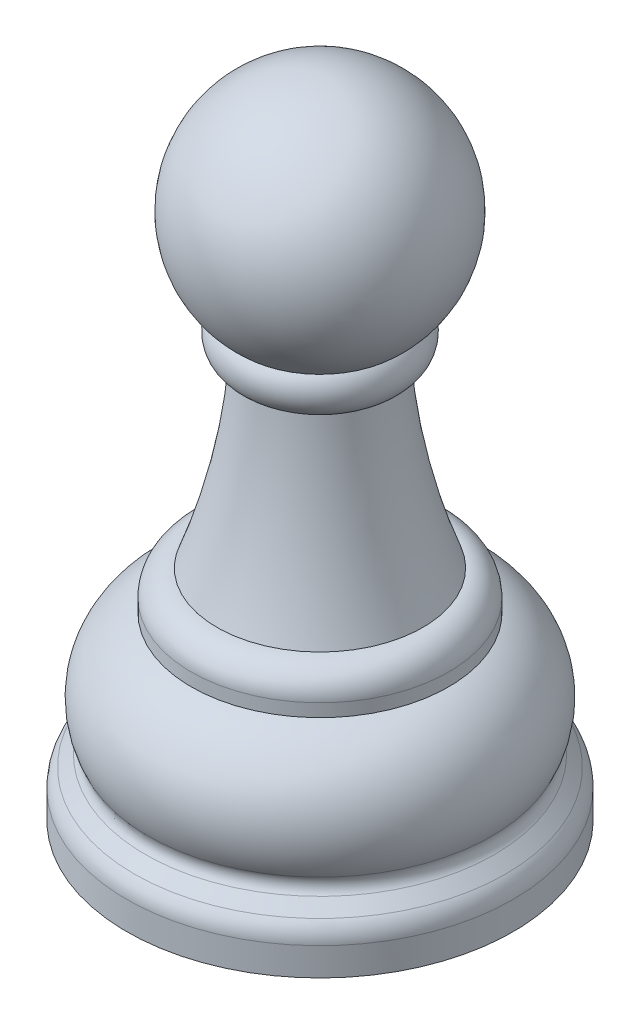
SolidWorks part; units mm, degrees
ref_plane "Front Plane" through (0, 0, 0) normal (0, 0, 1) x (1, 0, 0)
ref_plane "Top Plane" through (0, 0, 0) normal (0, 1, 0) x (1, 0, 0)
ref_plane "Right Plane" through (0, 0, 0) normal (1, 0, 0) x (0, 0, -1)
sketch "Sketch1" plane through (0, 0, 0) normal (0, 0, 1) x (1, 0, 0)
  line L0 (0, 0) -> (0, -50)
  line L1 (0, -50) -> (13, -50)
  line L4 (13, -45) -> (15, -47)
  line L5 (15, -47) -> (15, -50)
  line L6 (15, -50) -> (13, -50)
  line L12 (10, -36.03) -> (10, -35.03)
  arc A0 (10, -36.03) -> (13, -45) centre (8, -41.6856) cw
  arc A1 (8, -33.03) -> (10, -35.03) centre (8, -35.03) cw
  arc A2 (5, -19.03) -> (8, -33.03) centre (54.8864, -15.6615) ccw
  arc A3 (6, -15.77) -> (5, -19.03) centre (4.5005, -17.0934) cw
  arc A4 (6, -15.77) -> (0, 0) centre (0.0701, -8.9997) ccw
  dimension "D1" = 50
  dimension "D2" = 14
revolve "Revolve1" add sketch "Sketch1" angle 360 about L0
fillet "Fillet1" radius 2 1 edges at (-15, -47, 0)
fillet "Fillet2" radius 1 1 edges at (-13, -45, 0)
